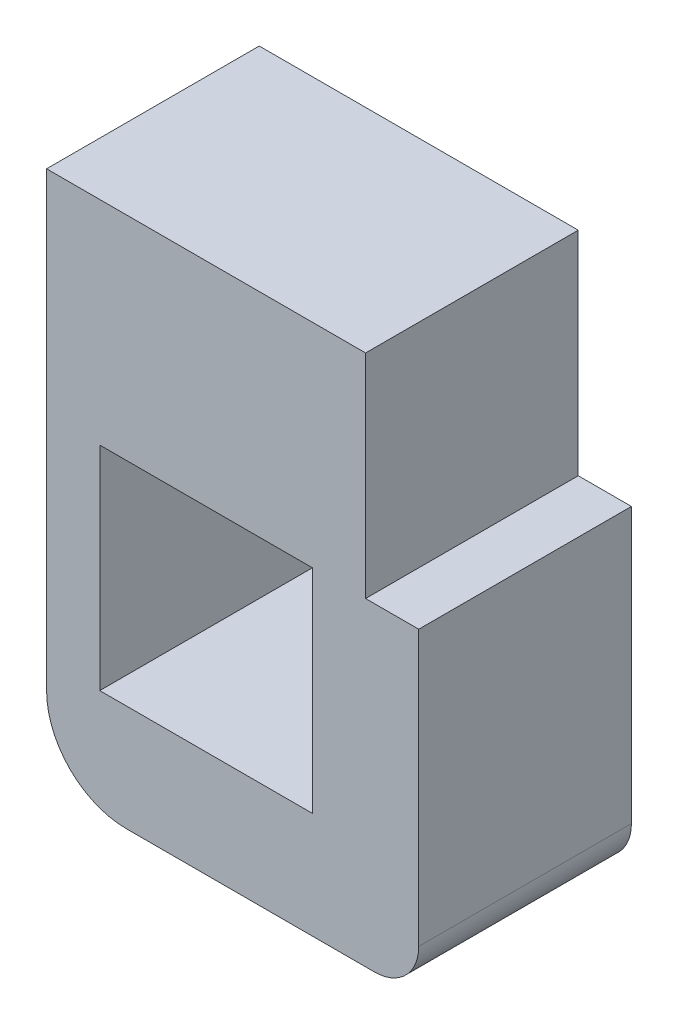
SolidWorks part; units mm, degrees
ref_plane "Plan de face" through (0, 0, 0) normal (0, 0, 1) x (1, 0, 0)
ref_plane "Plan de dessus" through (0, 0, 0) normal (0, 1, 0) x (1, 0, 0)
ref_plane "Plan de droite" through (0, 0, 0) normal (1, 0, 0) x (0, 0, -1)
sketch "Esquisse1" plane through (0, 0, 0) normal (0, 0, 1) x (1, 0, 0)
  line L0 (0, 0) -> (6, 0)
  line L1 (6, 0) -> (6, -4)
  line L2 (6, -4) -> (7, -4)
  line L3 (7, -4) -> (7, -9.1667)
  line L4 (6.1667, -10) -> (-0.1667, -10)
  line L5 (-1, -9.1667) -> (-1, -4)
  line L6 (-1, -4) -> (0, -4)
  line L7 (0, -4) -> (0, 0)
  line L8 (3, 1.2327) -> (3, -6) construction
  line L9 (1, -8) -> (5, -8)
  line L10 (1, -8) -> (1, -4)
  line L11 (1, -4) -> (5, -4)
  line L12 (5, -8) -> (5, -4)
  line L13 (1, -8) -> (5, -4) construction
  line L14 (1, -4) -> (5, -8) construction
  line L15 (7, -9.1667) -> (7, -10) construction
  line L16 (7, -10) -> (6.1667, -10) construction
  line L17 (5, -8) -> (7, -10) construction
  arc A0 (7, -9.1667) -> (6.1667, -10) centre (6.1667, -9.1667) cw
  arc A1 (-0.1667, -10) -> (-1, -9.1667) centre (-0.1667, -9.1667) cw
  point P11 (3, -6)
  dimension "D1" = 4
  dimension "D2" = 8
  dimension "D3" = 6
extrude "Boss.-Extru.1" add sketch "Esquisse1" along normal blind 4
sketch "Esquisse2" plane through (0, 0, 4) normal (0, 0, 1) x (1, 0, 0)
  line L0 (0, 0) -> (0, -10.6869)
  line L1 (0, -10.6869) -> (-3.1476, -9.8755)
  line L2 (-3.1476, -9.8755) -> (-3.0376, -0.7984)
  line L3 (-3.0376, -0.7984) -> (0, 0)
extrude "Enlèv. mat.-Extru.1" cut sketch "Esquisse2" against normal up to next
fillet "Congé2" radius 1.5 1 edges at (0, -10, 2)
